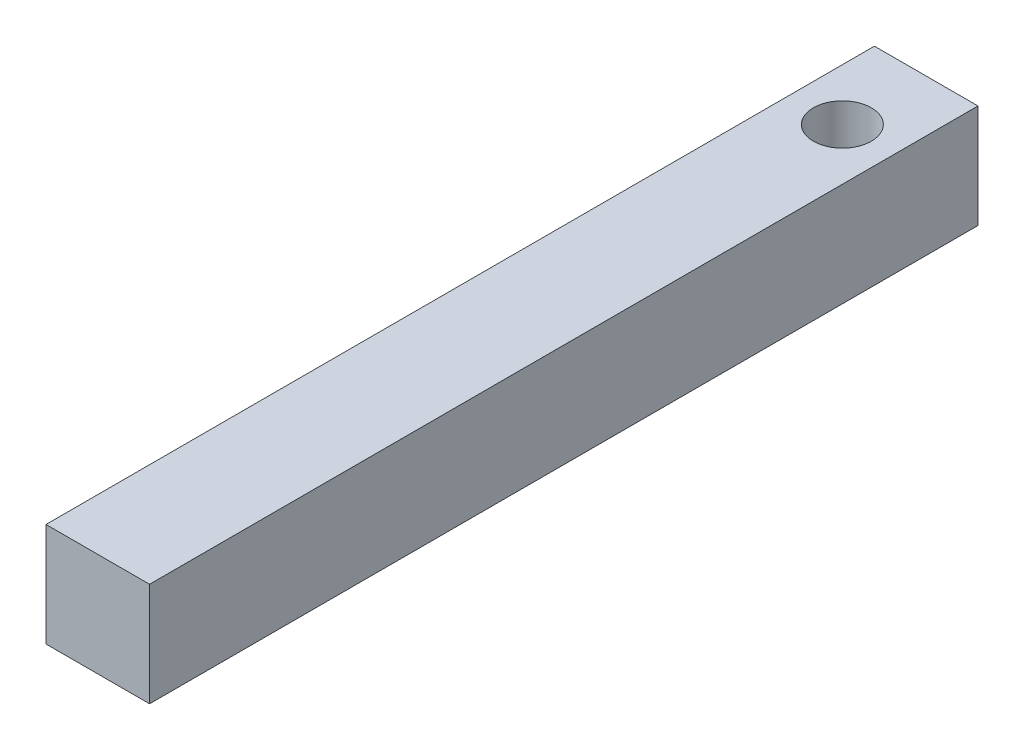
SolidWorks part; units mm, degrees
ref_plane "前视基准面" through (0, 0, 0) normal (0, 0, 1) x (1, 0, 0)
ref_plane "上视基准面" through (0, 0, 0) normal (0, 1, 0) x (1, 0, 0)
ref_plane "右视基准面" through (0, 0, 0) normal (1, 0, 0) x (0, 0, -1)
sketch "草图2" plane through (0, 0, 0) normal (0, 0, 1) x (1, 0, 0)
  line L1 (0, 0) -> (25.4, 0)
  line L2 (0, 0) -> (0, 25.4)
  line L3 (0, 25.4) -> (25.4, 25.4)
  line L4 (25.4, 0) -> (25.4, 25.4)
extrude "凸台-拉伸1" add sketch "草图2" along normal blind 203.2
ref_plane "基准面1" through (0, 25.4, 0) normal (0, 1, 0) x (1, 0, 0)
sketch "草图3" plane through (0, 25.4, 0) normal (0, 1, 0) x (1, 0, 0)
  line L0 (12.7, 0) -> (12.7, -20.574) construction
  line L1 (25.4, 0) -> (0, 0) construction
  circle A0 centre (12.7, -20.574) radius 7.112
extrude "切除-拉伸1" cut sketch "草图3" against normal through all
